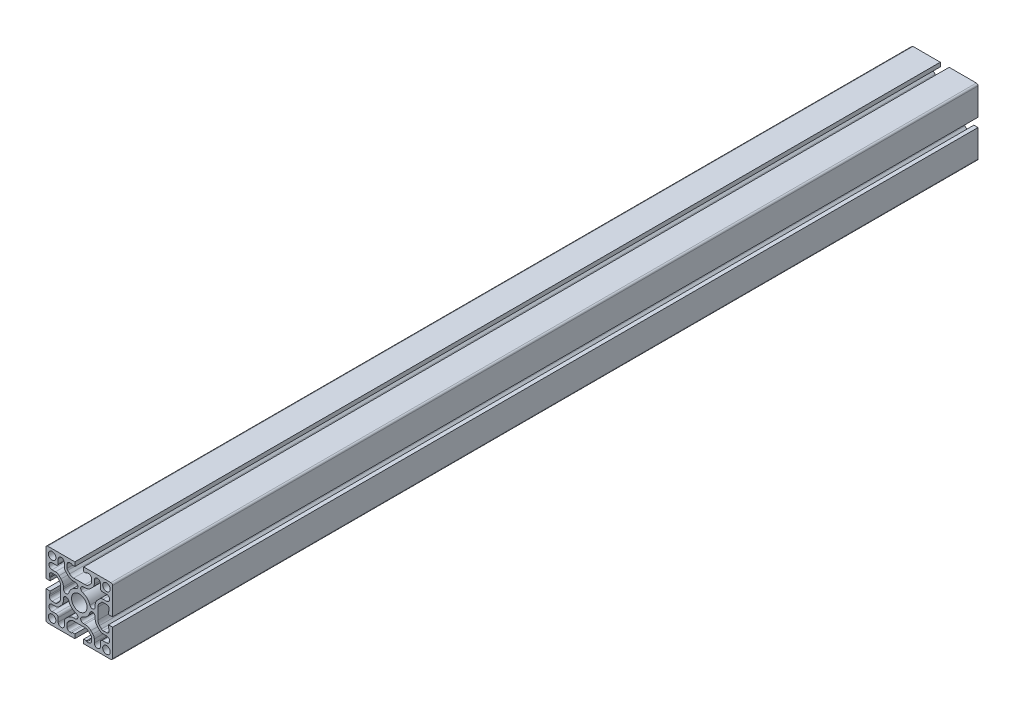
SolidWorks part; units mm, degrees
ref_plane "Płaszczyzna przednia" through (0, 0, 0) normal (0, 0, 1) x (1, 0, 0)
ref_plane "Płaszczyzna górna" through (0, 0, 0) normal (0, 1, 0) x (1, 0, 0)
ref_plane "Płaszczyzna prawa" through (0, 0, 0) normal (1, 0, 0) x (0, 0, -1)
ref_plane "Plane1" through (0, 0, 0) normal (0, 0, -1) x (-1, 0, 0)
sketch "Sketch1" plane through (0, 0, 0) normal (0, 0, -1) x (-1, 0, 0)
  line L0 (5.1034, -14.3) -> (3.6784, -14.3)
  line L1 (14.3, -3.6784) -> (14.3, -5.1134)
  line L2 (16.4818, -10.4017) -> (18.2431, -12.173)
  line L3 (21.434, -13.5) -> (24.6, -13.5)
  line L4 (24.6, -19) -> (21, -19)
  line L5 (19, -21) -> (19, -24.6)
  line L6 (13.5, -24.6) -> (13.5, -21.454)
  line L7 (12.182, -18.272) -> (10.4067, -16.4967)
  line L8 (-3.6784, -14.3) -> (-5.1034, -14.3)
  line L9 (-10.4067, -16.4967) -> (-12.182, -18.272)
  line L10 (-13.5, -21.454) -> (-13.5, -24.6)
  line L11 (-19, -24.6) -> (-19, -21)
  line L12 (-21, -19) -> (-24.6, -19)
  line L13 (-24.6, -13.5) -> (-21.434, -13.5)
  line L14 (-18.2431, -12.173) -> (-16.4818, -10.4017)
  line L15 (-14.3, -5.1134) -> (-14.3, -3.6784)
  line L16 (-5.1034, 14.3) -> (-3.6784, 14.3)
  line L17 (-14.3, 3.6784) -> (-14.3, 5.1134)
  line L18 (-16.4818, 10.4017) -> (-18.2431, 12.173)
  line L19 (-21.434, 13.5) -> (-24.6, 13.5)
  line L20 (-24.6, 19) -> (-21, 19)
  line L21 (-19, 21) -> (-19, 24.6)
  line L22 (-13.5, 24.6) -> (-13.5, 21.454)
  line L23 (-12.182, 18.272) -> (-10.4067, 16.4967)
  line L24 (3.6784, 14.3) -> (5.1034, 14.3)
  line L25 (10.4067, 16.4967) -> (12.182, 18.272)
  line L26 (13.5, 21.454) -> (13.5, 24.6)
  line L27 (19, 24.6) -> (19, 21)
  line L28 (21, 19) -> (24.6, 19)
  line L29 (24.6, 13.5) -> (21.434, 13.5)
  line L30 (18.2431, 12.173) -> (16.4818, 10.4017)
  line L31 (14.3, 5.1134) -> (14.3, 3.6784)
  line L32 (5.1, 16.8) -> (-5.11, 16.8)
  line L33 (-8.6455, 18.2645) -> (-10.42, 20.04)
  line L34 (-11, 21.45) -> (-11, 24.5)
  line L35 (-8.5, 27) -> (-7.07, 27)
  line L36 (-6.57, 26.5) -> (-6.57, 26.3)
  line L37 (-6.57, 26.3) -> (-4, 26.3)
  line L38 (-4, 26.3) -> (-4, 30)
  line L39 (-4, 30) -> (-28.5, 30)
  line L40 (-30, 28.5) -> (-30, 4)
  line L41 (-30, 4) -> (-26.3, 4)
  line L42 (-26.3, 4) -> (-26.3, 6.57)
  line L43 (-26.3, 6.57) -> (-26.5, 6.57)
  line L44 (-27, 7.07) -> (-27, 8.5)
  line L45 (-24.5, 11) -> (-21.45, 11)
  line L46 (-20.0358, 10.4142) -> (-18.27, 8.65)
  line L47 (-16.8, 5.11) -> (-16.8, -5.1)
  line L48 (-18.2645, -8.6355) -> (-20.04, -10.41)
  line L49 (-21.45, -11) -> (-24.5, -11)
  line L50 (-27, -8.5) -> (-27, -7.07)
  line L51 (-26.5, -6.57) -> (-26.3, -6.57)
  line L52 (-26.3, -6.57) -> (-26.3, -4)
  line L53 (-26.3, -4) -> (-30, -4)
  line L54 (-30, -4) -> (-30, -28.5)
  line L55 (-28.5, -30) -> (-4, -30)
  line L56 (-4, -30) -> (-4, -26.3)
  line L57 (-4, -26.3) -> (-6.57, -26.3)
  line L58 (-6.57, -26.3) -> (-6.57, -26.5)
  line L59 (-7.07, -27) -> (-8.5, -27)
  line L60 (-11, -24.5) -> (-11, -21.45)
  line L61 (-10.4142, -20.0358) -> (-8.65, -18.26)
  line L62 (-5.11, -16.8) -> (5.1, -16.8)
  line L63 (8.64, -18.26) -> (10.41, -20.03)
  line L64 (11, -21.45) -> (11, -24.5)
  line L65 (8.5, -27) -> (7.07, -27)
  line L66 (6.57, -26.5) -> (6.57, -26.3)
  line L67 (6.57, -26.3) -> (4, -26.3)
  line L68 (4, -26.3) -> (4, -30)
  line L69 (4, -30) -> (28.5, -30)
  line L70 (30, -28.5) -> (30, -4)
  line L71 (30, -4) -> (26.3, -4)
  line L72 (26.3, -4) -> (26.3, -6.57)
  line L73 (26.3, -6.57) -> (26.5, -6.57)
  line L74 (27, -7.07) -> (27, -8.5)
  line L75 (24.5, -11) -> (21.45, -11)
  line L76 (20.0358, -10.4142) -> (18.26, -8.64)
  line L77 (16.8, -5.1) -> (16.8, 5.11)
  line L78 (18.26, 8.65) -> (20.0358, 10.4142)
  line L79 (21.45, 11) -> (24.5, 11)
  line L80 (27, 8.5) -> (27, 7.07)
  line L81 (26.5, 6.57) -> (26.3, 6.57)
  line L82 (26.3, 6.57) -> (26.3, 4)
  line L83 (26.3, 4) -> (30, 4)
  line L84 (30, 4) -> (30, 28.5)
  line L85 (28.5, 30) -> (4, 30)
  line L86 (4, 30) -> (4, 26.3)
  line L87 (4, 26.3) -> (6.57, 26.3)
  line L88 (6.57, 26.3) -> (6.57, 26.5)
  line L89 (7.07, 27) -> (8.5, 27)
  line L90 (11, 24.5) -> (11, 21.45)
  line L91 (10.4142, 20.0358) -> (8.64, 18.27)
  circle A0 centre (-24.5, 24.5) radius 3.4
  circle A1 centre (24.5, 24.5) radius 3.4
  circle A2 centre (-24.5, -24.49) radius 3.4
  circle A3 centre (24.5, -24.49) radius 3.4
  circle A4 centre (0, 0) radius 7
  arc A5 (3.6784, -14.3) -> (2.9597, -9.552) centre (3.6784, -11.8716) cw
  arc A6 (2.9597, -9.552) -> (9.552, -2.9597) centre (0, 0) ccw
  arc A7 (9.552, -2.9597) -> (14.3, -3.6784) centre (11.8716, -3.6784) cw
  arc A8 (14.3, -5.1134) -> (16.4818, -10.4017) centre (21.8, -5.1134) ccw
  arc A9 (18.2431, -12.173) -> (21.434, -13.5) centre (21.434, -9) ccw
  arc A10 (24.6, -13.5) -> (24.6, -19) centre (24.6, -16.25) cw
  arc A11 (21, -19) -> (19, -21) centre (21, -21) ccw
  arc A12 (19, -24.6) -> (13.5, -24.6) centre (16.25, -24.6) cw
  arc A13 (13.5, -21.454) -> (12.182, -18.272) centre (9, -21.454) ccw
  arc A14 (10.4067, -16.4967) -> (5.1034, -14.3) centre (5.1034, -21.8) ccw
  arc A15 (-9.552, -2.9597) -> (-2.9597, -9.552) centre (0, 0) ccw
  arc A16 (-2.9597, -9.552) -> (-3.6784, -14.3) centre (-3.6784, -11.8716) cw
  arc A17 (-5.1034, -14.3) -> (-10.4067, -16.4967) centre (-5.1034, -21.8) ccw
  arc A18 (-12.182, -18.272) -> (-13.5, -21.454) centre (-9, -21.454) ccw
  arc A19 (-13.5, -24.6) -> (-19, -24.6) centre (-16.25, -24.6) cw
  arc A20 (-19, -21) -> (-21, -19) centre (-21, -21) ccw
  arc A21 (-24.6, -19) -> (-24.6, -13.5) centre (-24.6, -16.25) cw
  arc A22 (-21.434, -13.5) -> (-18.2431, -12.173) centre (-21.434, -9) ccw
  arc A23 (-16.4818, -10.4017) -> (-14.3, -5.1134) centre (-21.8, -5.1134) ccw
  arc A24 (-14.3, -3.6784) -> (-9.552, -2.9597) centre (-11.8716, -3.6784) cw
  arc A25 (-3.6784, 14.3) -> (-2.9597, 9.552) centre (-3.6784, 11.8716) cw
  arc A26 (-2.9597, 9.552) -> (-9.552, 2.9597) centre (0, 0) ccw
  arc A27 (-9.552, 2.9597) -> (-14.3, 3.6784) centre (-11.8716, 3.6784) cw
  arc A28 (-14.3, 5.1134) -> (-16.4818, 10.4017) centre (-21.8, 5.1134) ccw
  arc A29 (-18.2431, 12.173) -> (-21.434, 13.5) centre (-21.434, 9) ccw
  arc A30 (-24.6, 13.5) -> (-24.6, 19) centre (-24.6, 16.25) cw
  arc A31 (-21, 19) -> (-19, 21) centre (-21, 21) ccw
  arc A32 (-19, 24.6) -> (-13.5, 24.6) centre (-16.25, 24.6) cw
  arc A33 (-13.5, 21.454) -> (-12.182, 18.272) centre (-9, 21.454) ccw
  arc A34 (-10.4067, 16.4967) -> (-5.1034, 14.3) centre (-5.1034, 21.8) ccw
  arc A35 (9.552, 2.9597) -> (2.9597, 9.552) centre (0, 0) ccw
  arc A36 (2.9597, 9.552) -> (3.6784, 14.3) centre (3.6784, 11.8716) cw
  arc A37 (5.1034, 14.3) -> (10.4067, 16.4967) centre (5.1034, 21.8) ccw
  arc A38 (12.182, 18.272) -> (13.5, 21.454) centre (9, 21.454) ccw
  arc A39 (13.5, 24.6) -> (19, 24.6) centre (16.25, 24.6) cw
  arc A40 (19, 21) -> (21, 19) centre (21, 21) ccw
  arc A41 (24.6, 19) -> (24.6, 13.5) centre (24.6, 16.25) cw
  arc A42 (21.434, 13.5) -> (18.2431, 12.173) centre (21.434, 9) ccw
  arc A43 (16.4818, 10.4017) -> (14.3, 5.1134) centre (21.8, 5.1134) ccw
  arc A44 (14.3, 3.6784) -> (9.552, 2.9597) centre (11.8716, 3.6784) cw
  arc A45 (-5.11, 16.8) -> (-8.6455, 18.2645) centre (-5.11, 21.8) cw
  arc A46 (-10.42, 20.04) -> (-11, 21.45) centre (-8.9925, 21.4515) cw
  arc A47 (-11, 24.5) -> (-8.5, 27) centre (-8.5, 24.5) cw
  arc A48 (-7.07, 27) -> (-6.57, 26.5) centre (-7.07, 26.5) cw
  arc A49 (-28.5, 30) -> (-30, 28.5) centre (-28.5, 28.5) ccw
  arc A50 (-26.5, 6.57) -> (-27, 7.07) centre (-26.5, 7.07) cw
  arc A51 (-27, 8.5) -> (-24.5, 11) centre (-24.5, 8.5) cw
  arc A52 (-21.45, 11) -> (-20.0358, 10.4142) centre (-21.45, 9) cw
  arc A53 (-18.27, 8.65) -> (-16.8, 5.11) centre (-21.7951, 5.111) cw
  arc A54 (-16.8, -5.1) -> (-18.2645, -8.6355) centre (-21.8, -5.1) cw
  arc A55 (-20.04, -10.41) -> (-21.45, -11) centre (-21.4424, -9.0384) cw
  arc A56 (-24.5, -11) -> (-27, -8.5) centre (-24.5, -8.5) cw
  arc A57 (-27, -7.07) -> (-26.5, -6.57) centre (-26.5, -7.07) cw
  arc A58 (-30, -28.5) -> (-28.5, -30) centre (-28.5, -28.5) ccw
  arc A59 (-6.57, -26.5) -> (-7.07, -27) centre (-7.07, -26.5) cw
  arc A60 (-8.5, -27) -> (-11, -24.5) centre (-8.5, -24.5) cw
  arc A61 (-11, -21.45) -> (-10.4142, -20.0358) centre (-9, -21.45) cw
  arc A62 (-8.65, -18.26) -> (-5.11, -16.8) centre (-5.1017, -21.8418) cw
  arc A63 (5.1, -16.8) -> (8.64, -18.26) centre (5.0917, -21.8418) cw
  arc A64 (10.41, -20.03) -> (11, -21.45) centre (8.9927, -21.4515) cw
  arc A65 (11, -24.5) -> (8.5, -27) centre (8.5, -24.5) cw
  arc A66 (7.07, -27) -> (6.57, -26.5) centre (7.07, -26.5) cw
  arc A67 (28.5, -30) -> (30, -28.5) centre (28.5, -28.5) ccw
  arc A68 (26.5, -6.57) -> (27, -7.07) centre (26.5, -7.07) cw
  arc A69 (27, -8.5) -> (24.5, -11) centre (24.5, -8.5) cw
  arc A70 (21.45, -11) -> (20.0358, -10.4142) centre (21.45, -9) cw
  arc A71 (18.26, -8.64) -> (16.8, -5.1) centre (21.8418, -5.0917) cw
  arc A72 (16.8, 5.11) -> (18.26, 8.65) centre (21.8418, 5.1017) cw
  arc A73 (20.0358, 10.4142) -> (21.45, 11) centre (21.45, 9) cw
  arc A74 (24.5, 11) -> (27, 8.5) centre (24.5, 8.5) cw
  arc A75 (27, 7.07) -> (26.5, 6.57) centre (26.5, 7.07) cw
  arc A76 (30, 28.5) -> (28.5, 30) centre (28.5, 28.5) ccw
  arc A77 (6.57, 26.5) -> (7.07, 27) centre (7.0699, 26.5001) cw
  arc A78 (8.5, 27) -> (11, 24.5) centre (8.5, 24.5) cw
  arc A79 (11, 21.45) -> (10.4142, 20.0358) centre (9, 21.45) cw
  arc A80 (8.64, 18.27) -> (5.1, 16.8) centre (5.101, 21.7951) cw
extrude "Boss-Extrude1" add sketch "Sketch1" against normal blind 780
